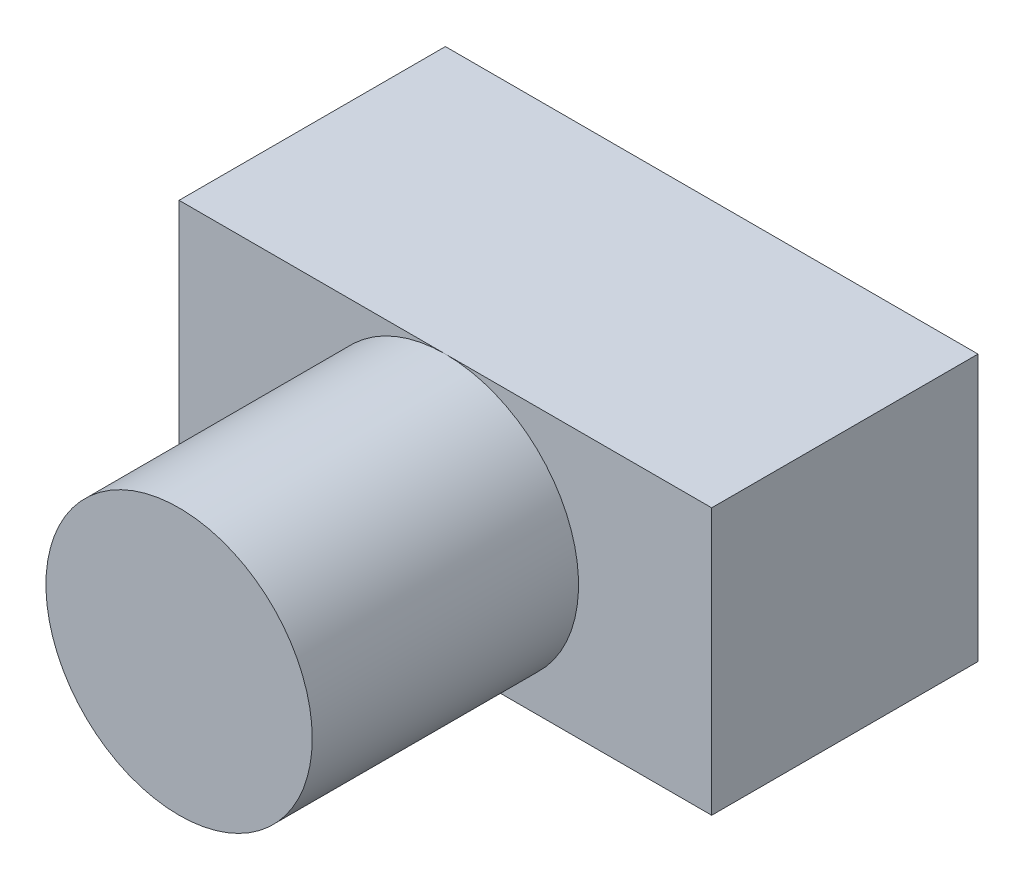
SolidWorks part; units mm, degrees
ref_plane "Front Plane" through (0, 0, 0) normal (0, 0, 1) x (1, 0, 0)
ref_plane "Top Plane" through (0, 0, 0) normal (0, 1, 0) x (1, 0, 0)
ref_plane "Right Plane" through (0, 0, 0) normal (1, 0, 0) x (0, 0, -1)
sketch "Sketch1" plane through (0, 0, 0) normal (0, 0, 1) x (1, 0, 0)
  line L1 (-10, 5) -> (0, 5)
  line L2 (-10, 5) -> (-10, 0)
  line L3 (-10, 0) -> (0, 0)
  line L4 (0, 5) -> (0, 0)
  dimension "D1" = 5
  dimension "D2" = 10
extrude "Boss-Extrude1" add sketch "Sketch1" along normal blind 5
sketch "Sketch2" plane through (0, 0, 5) normal (0, 0, 1) x (1, 0, 0)
  line L0 (0, 5) -> (-10, 5) construction
  line L1 (0, 5) -> (-10, 5) construction
  circle A0 centre (-5, 2.5) radius 2.5
  point P4 (0, 0)
  point P5 (-5, 5)
  dimension "D1" = 5
extrude "Boss-Extrude2" add sketch "Sketch2" along normal blind 5
